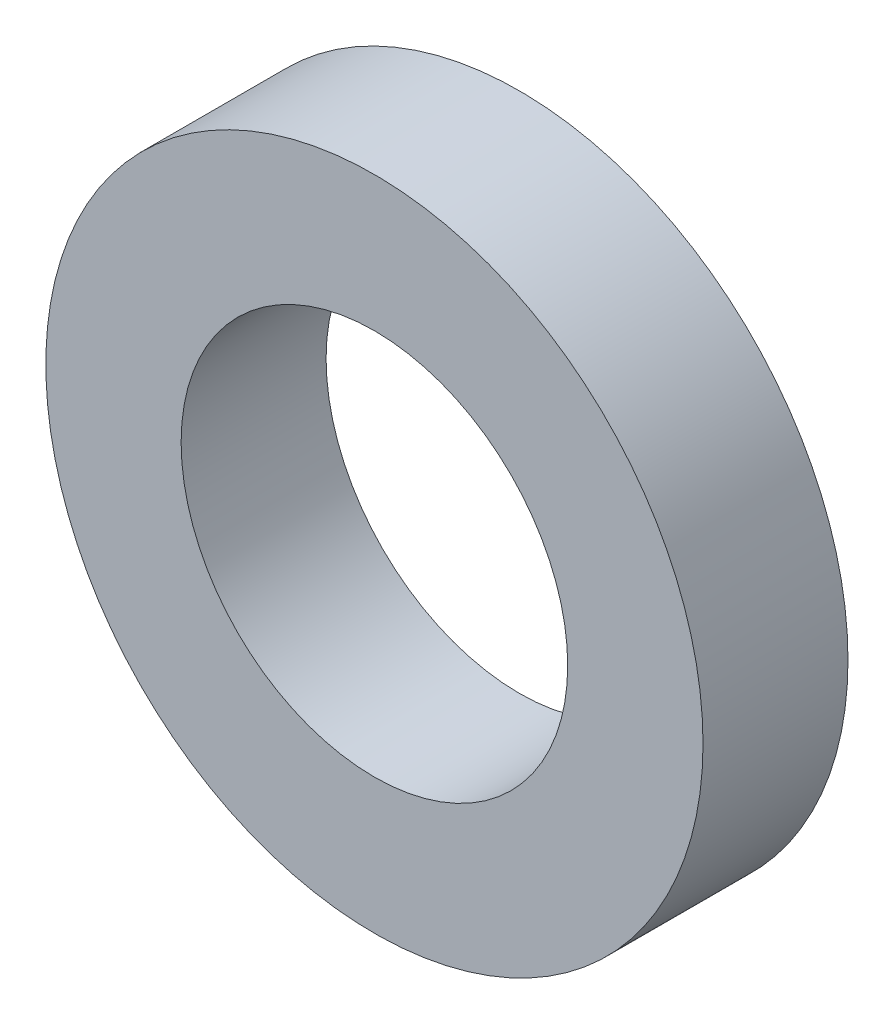
SolidWorks part; units mm, degrees
ref_plane "前视基准面" through (0, 0, 0) normal (0, 0, 1) x (1, 0, 0)
ref_plane "上视基准面" through (0, 0, 0) normal (0, 1, 0) x (1, 0, 0)
ref_plane "右视基准面" through (0, 0, 0) normal (1, 0, 0) x (0, 0, -1)
sketch "草图1" plane through (0, 0, 0) normal (0, 0, 1) x (1, 0, 0)
  circle A0 centre (0, 0) radius 34
  circle A1 centre (0, 0) radius 20
  dimension "D1" = 68
  dimension "D2" = 40
extrude "拉伸1" add sketch "草图1" along normal blind 15
